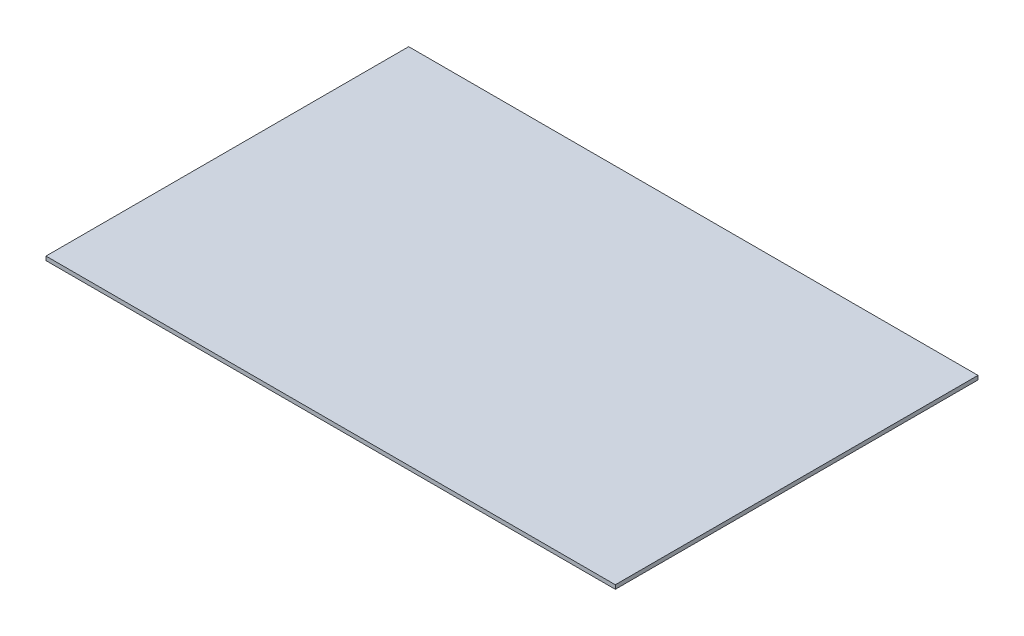
SolidWorks part; units mm, degrees
ref_plane "Piano frontale" through (0, 0, 0) normal (0, 0, 1) x (1, 0, 0)
ref_plane "Piano superiore" through (0, 0, 0) normal (0, 1, 0) x (1, 0, 0)
ref_plane "Piano destro" through (0, 0, 0) normal (1, 0, 0) x (0, 0, -1)
sketch "Schizzo1" plane through (0, 0, 0) normal (0, 1, 0) x (1, 0, 0)
  line L1 (1428.5, -910) -> (-1428.5, -910)
  line L2 (1428.5, -910) -> (1428.5, 910)
  line L3 (1428.5, 910) -> (-1428.5, 910)
  line L4 (-1428.5, -910) -> (-1428.5, 910)
  line L5 (1428.5, -910) -> (-1428.5, 910) construction
  line L6 (1428.5, 910) -> (-1428.5, -910) construction
  point P0 (0, 0)
  dimension "D1" = 1820
  dimension "D2" = 2857
extrude "Estrusione-Estrusione1" add sketch "Schizzo1" along normal blind 20
